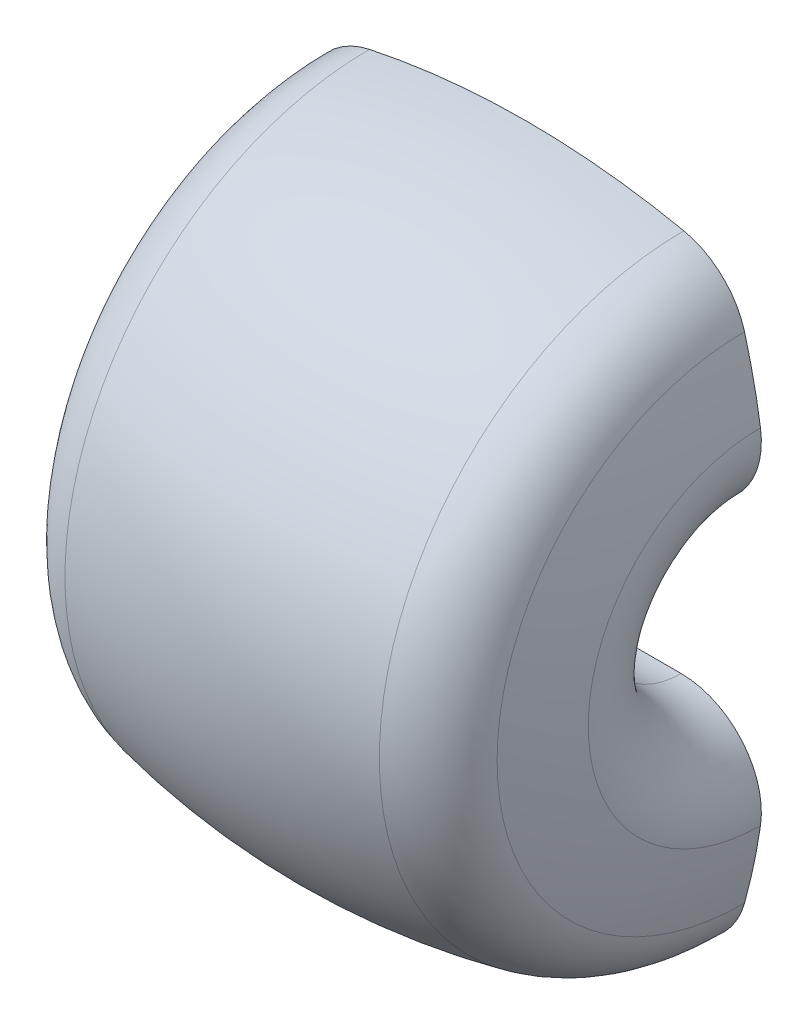
SolidWorks part; units mm, degrees
ref_plane "前视基准面" through (0, 0, 0) normal (0, 0, 1) x (1, 0, 0)
ref_plane "上视基准面" through (0, 0, 0) normal (0, 1, 0) x (1, 0, 0)
ref_plane "右视基准面" through (0, 0, 0) normal (1, 0, 0) x (0, 0, -1)
other "Configuration Table"
sketch "草图1" plane through (0, 0, 0) normal (0, 0, 1) x (1, 0, 0)
  line L0 (-17.5, 0) -> (17.5, 0) construction
  line L1 (0, 20) -> (0, 5) construction
  line L3 (-15, 5) -> (15, 5)
  arc A2 (12.6691, 18.2758) -> (-12.6691, 18.2758) centre (0, -27.4063) ccw
  arc A3 (-15, 5) -> (-12.6691, 18.2758) centre (23.9716, 5) cw
  arc A4 (15, 5) -> (12.6691, 18.2758) centre (-23.9716, 5) ccw
  point P3 (0, 0)
  dimension "D4" = 30
revolve "旋转1" add sketch "草图1" angle 180 about L0
fillet "圆角1" radius 5 2 edges at (12.6691, 0, 18.2758) (-12.6691, 0, 18.2758)
fillet "圆角2" radius 5 2 edges at (15, 0, 5) (-15, 0, 5)
sketch "草图2" plane through (0, 0, 0) normal (0, 0, -1) x (-1, 0, 0)
  line L1 (-6, 14.5) -> (6, 14.5)
  line L2 (-6, 14.5) -> (-6, 9.5)
  line L3 (-6, 9.5) -> (6, 9.5)
  line L4 (6, 14.5) -> (6, 9.5)
  line L5 (-6, 14.5) -> (6, 9.5) construction
  line L6 (-6, 9.5) -> (6, 14.5) construction
  line L7 (-6, -9.5) -> (6, -9.5)
  line L8 (-6, -9.5) -> (-6, -14.5)
  line L9 (-6, -14.5) -> (6, -14.5)
  line L10 (6, -9.5) -> (6, -14.5)
  line L11 (-6, -9.5) -> (6, -14.5) construction
  line L12 (-6, -14.5) -> (6, -9.5) construction
  point P0 (0, 12)
  point P5 (0, -12)
  dimension "D1" = 12
  dimension "D2" = 12
  dimension "D3" = 5
  dimension "D4" = 12
  dimension "D5" = 12
  dimension "D6" = 5
extrude "切除-拉伸1" cut sketch "草图2" against normal blind 6
